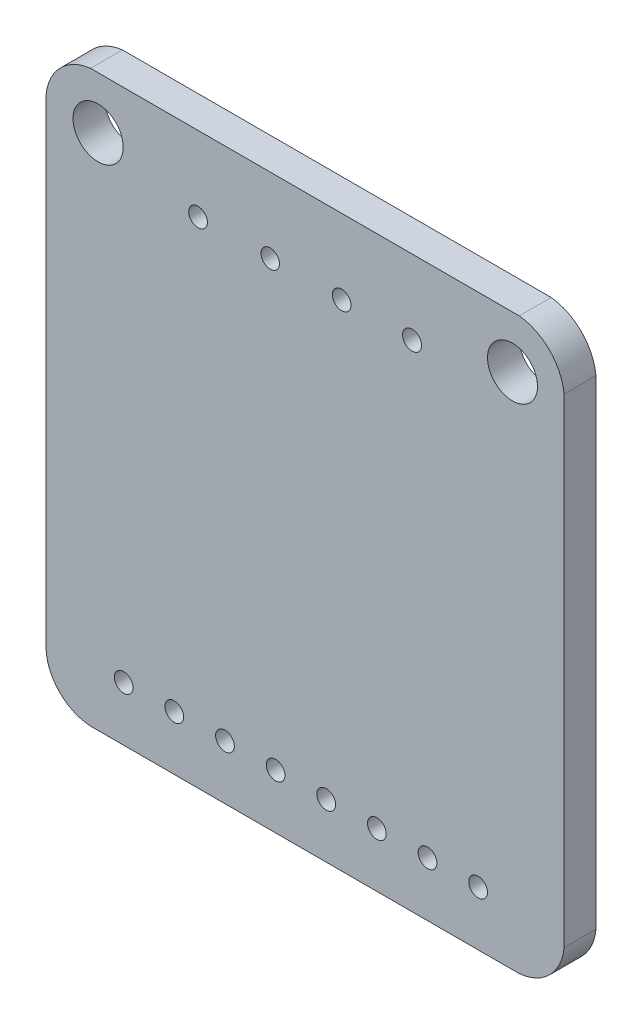
SolidWorks part; units mm, degrees
ref_plane "Plan de face" through (0, 0, 0) normal (0, 0, 1) x (1, 0, 0)
ref_plane "Plan de dessus" through (0, 0, 0) normal (0, 1, 0) x (1, 0, 0)
ref_plane "Plan de droite" through (0, 0, 0) normal (1, 0, 0) x (0, 0, -1)
sketch "Esquisse2" plane through (0, 0, 0) normal (0, 0, 1) x (1, 0, 0)
  line L0 (-13.0057, 11.1802) -> (12.9943, 11.1802) construction
  line L1 (-10.7637, 13.565) -> (10.7458, 13.565)
  line L2 (-12.9958, 11.2933) -> (-12.9958, -12.7509)
  line L3 (-10.7637, -15.0118) -> (10.7458, -15.0118)
  line L4 (12.9941, -12.7509) -> (12.9941, 11.2933)
  circle A0 centre (-5.3682, 9.803) radius 0.4679
  circle A1 centre (-1.7475, 9.8086) radius 0.4625
  circle A2 centre (1.8366, 9.8026) radius 0.468
  circle A3 centre (5.3681, 9.8235) radius 0.4776
  circle A4 centre (-9.0981, -12.281) radius 0.4702
  circle A5 centre (-6.5581, -12.281) radius 0.4702
  circle A6 centre (-4.0181, -12.281) radius 0.4702
  circle A7 centre (-1.4781, -12.281) radius 0.4702
  circle A8 centre (1.0619, -12.281) radius 0.4702
  circle A9 centre (3.6019, -12.281) radius 0.4702
  circle A10 centre (6.1419, -12.281) radius 0.4702
  circle A11 centre (8.6819, -12.281) radius 0.4702
  circle A12 centre (-10.3812, 10.9504) radius 1.2592
  circle A13 centre (10.4052, 10.9544) radius 1.2547
  arc A14 (12.9941, 11.2933) -> (10.7458, 13.565) centre (10.466, 11.0397) ccw
  arc A15 (-10.7637, 13.565) -> (-12.9958, 11.2933) centre (-10.4709, 11.0448) ccw
  arc A16 (-12.9958, -12.7509) -> (-10.7637, -15.0118) centre (-10.64, -12.6573) ccw
  arc A17 (12.9941, -12.7509) -> (10.7458, -15.0118) centre (10.518, -12.537) cw
  dimension "D1" = 26
  dimension "D2" = 8
extrude "Boss.-Extru.1" add sketch "Esquisse2" along normal blind 1.6
